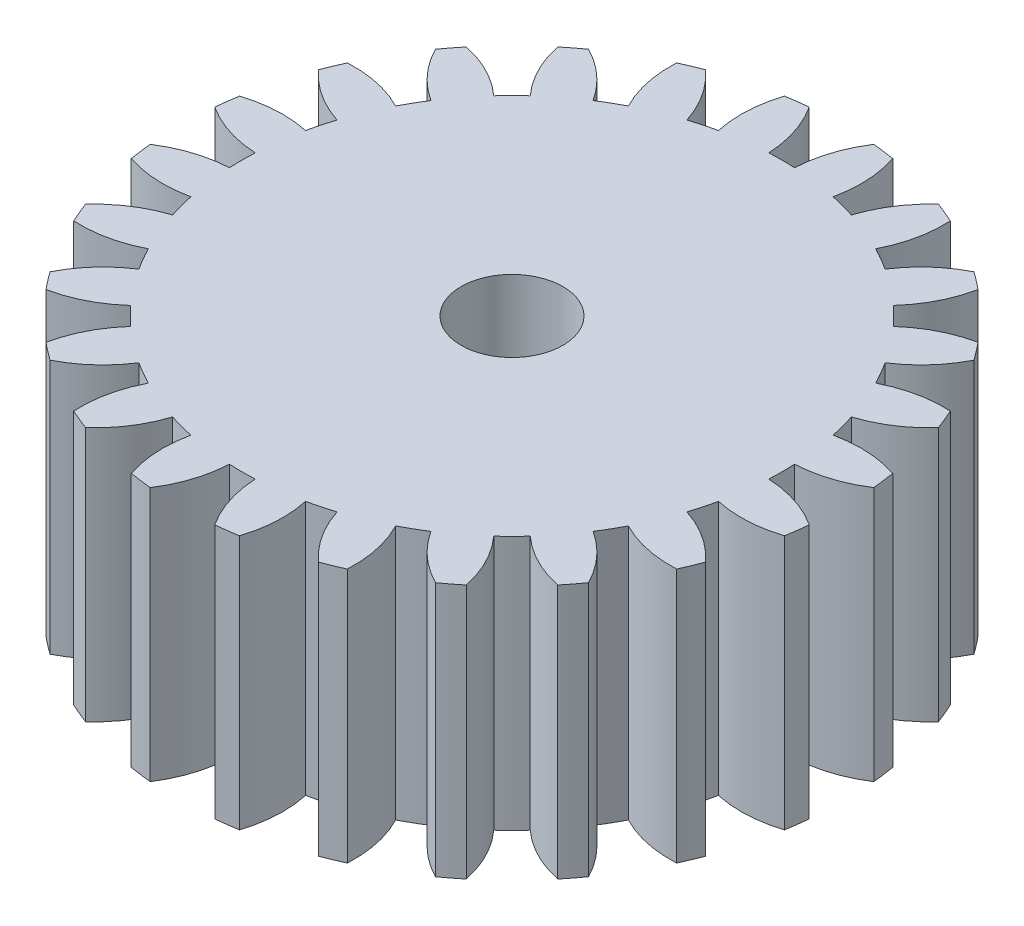
SolidWorks part; units mm, degrees
ref_plane "Front Plane" through (0, 0, 0) normal (0, 0, 1) x (1, 0, 0)
ref_plane "Top Plane" through (0, 0, 0) normal (0, 1, 0) x (1, 0, 0)
ref_plane "Right Plane" through (0, 0, 0) normal (1, 0, 0) x (0, 0, -1)
sketch "Sketch1" plane through (0, 0, 0) normal (0, 1, 0) x (1, 0, 0)
  circle A0 centre (0, 0) radius 6
  circle A1 centre (0, 0) radius 6.5
  circle A2 centre (0, 0) radius 5.3
  dimension "D1" = 12
  dimension "D2" = 13
  dimension "D3" = 1.2
extrude "Boss-Extrude1" add sketch "Sketch1" along normal mid plane 5 contours A1 A0 | A0 A2 | A2
sketch "Sketch3" plane through (0, 0, 0) normal (0, 1, 0) x (1, 0, 0)
  line L0 (0, 0) -> (0, 6.5) construction
  line L1 (-0.3924, 5.9872) -> (0.3924, 5.9872) construction
  line L2 (-0.253, 5.294) -> (0, 0) construction
  line L3 (0, 4.909) -> (-1.017, 7.7032) construction
  line L4 (0, 0) -> (0.8484, 6.4444) construction
  line L5 (0.3924, 5.9872) -> (1.1705, 5.8847) construction
  circle A0 centre (0, 0) radius 6.5 construction
  arc A1 (-2.0974, 7.4816) -> (-0.253, 5.294) centre (-2.606, 5.1815) cw
  arc A2 (2.0974, 7.4816) -> (0.253, 5.294) centre (2.606, 5.1815) ccw
  circle A3 centre (0, 0) radius 5.3 construction
  arc A4 (0.253, 5.294) -> (-0.253, 5.294) centre (0, 0) ccw
  circle A5 centre (0, 0) radius 6 construction
  circle A6 centre (0, 0) radius 6.5 construction
  circle A7 centre (0, 0) radius 7.77
  arc A8 (2.0974, 7.4816) -> (-2.0974, 7.4816) centre (0, 0) ccw
  dimension "D2" = 20
  dimension "D3" = 7.5
  dimension "D1" = 1.27
extrude "Cut-Extrude1" cut sketch "Sketch3" against normal through all both and the other way through all
fillet "Fillet2" [suppressed] radius 0.15
pattern_circular "CirPattern1" count 24 over 360 about axis through (0, 0, 0) along (0, 1, 0) of "Cut-Extrude1", "Fillet2"
sketch "Sketch4" plane through (0, 0, 0) normal (0, 1, 0) x (1, 0, 0)
  circle A0 centre (0, 0) radius 1
  dimension "D1" = 2
extrude "Cut-Extrude2" cut sketch "Sketch4" along normal through all both and the other way through all
equation "\"Module\"= .5"
equation "\"Number of Teeth\"= 24"
equation "\"D1@Sketch1\"=\"Module\"* \"Number of Teeth\""
equation "\"D2@Sketch1\"=(\"Number of Teeth\" + 2) * \"Module\""
equation "\"D3@Sketch1\"=\"Module\" * if( \"Module\" => 1.25, 2.25, 2.4)"
equation "\"D3@Sketch3\"=180 / \"Number of Teeth\""
equation "\"D1@Fillet2\"=.3 * \"Module\""
equation "\"D1@CirPattern1\"=\"Number of Teeth\""
